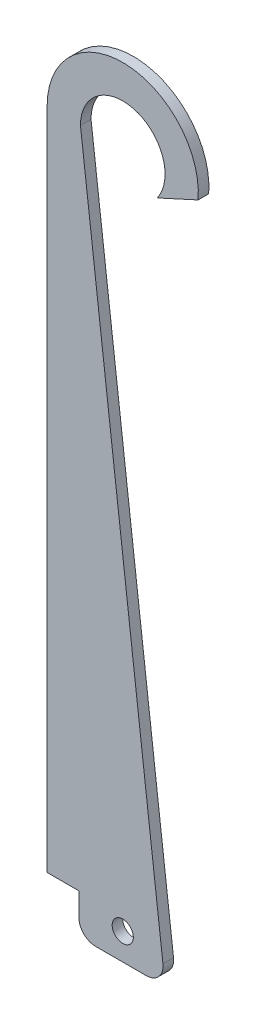
SolidWorks part; units mm, degrees
ref_plane "Front Plane" through (0, 0, 0) normal (0, 0, 1) x (1, 0, 0)
ref_plane "Top Plane" through (0, 0, 0) normal (0, 1, 0) x (1, 0, 0)
ref_plane "Right Plane" through (0, 0, 0) normal (1, 0, 0) x (0, 0, -1)
sketch "Sketch1" plane through (0, 0, 0) normal (0, 0, 1) x (1, 0, 0)
  line L0 (-17.3574, -1.7396) -> (-17.3574, 404.6604) construction
  line L1 (3.3311, 389.9246) -> (27.9099, 401.1627)
  line L2 (-62.7596, 404.6604) -> (-62.7596, 6.0902)
  line L5 (-43.7153, -17.7858) -> (-43.7153, 6.0902)
  line L6 (-43.7153, 6.0902) -> (-62.7596, 6.0902)
  line L7 (-42.7574, 404.6604) -> (8.1257, -17.7858)
  line L8 (8.1257, -17.7858) -> (-43.7153, -17.7858)
  circle A0 centre (-17.3574, 404.6604) radius 25.4 construction
  arc A1 (8.0426, 404.6604) -> (-42.7574, 404.6604) centre (-17.3574, 404.6604) ccw
  arc A2 (8.0426, 404.6604) -> (3.3311, 389.9246) centre (-17.3574, 404.6604) cw
  arc A3 (27.9099, 401.1627) -> (-62.7596, 404.6604) centre (-17.3574, 404.6604) ccw
  circle A4 centre (-17.3574, -1.7396) radius 6.35
  dimension "D2" = 50.8
  dimension "D3" = 12.7
  dimension "D5" = 23.876
  dimension "D1" = 406.4
  dimension "D6" = 19.0443
extrude "Boss-Extrude1" add sketch "Sketch1" along normal blind 6.35
fillet "Fillet1" radius 10 2 edges at (8.1257, -17.7858, 3.175) (-43.7153, -17.7858, 3.175)
